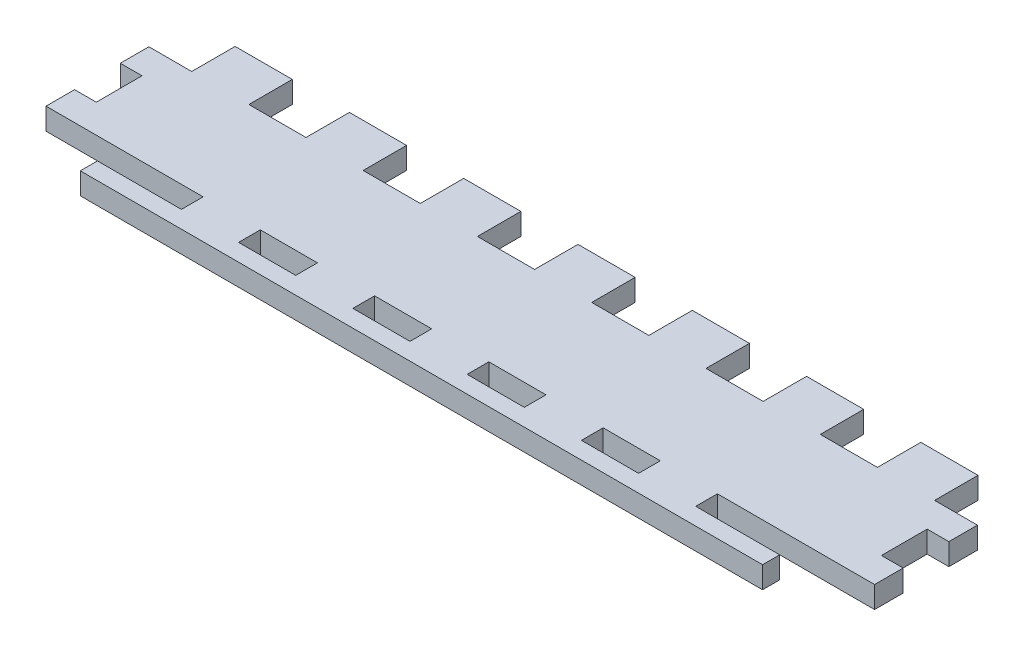
SolidWorks part; units mm, degrees
material "Maple"
ref_plane "Front Plane" through (0, 0, 0) normal (0, 0, 1) x (1, 0, 0)
ref_plane "Top Plane" through (0, 0, 0) normal (0, 1, 0) x (1, 0, 0)
ref_plane "Right Plane" through (0, 0, 0) normal (1, 0, 0) x (0, 0, -1)
sketch "Sketch1" plane through (0, 0, 0) normal (0, 1, 0) x (1, 0, 0)
  line L1 (0, 0) -> (145, 0)
  line L2 (0, 0) -> (0, -18)
  line L3 (0, -18) -> (145, -18)
  line L4 (145, 0) -> (145, -18)
  dimension "D1" = 145
  dimension "D2" = 18
extrude "Boss-Extrude1" add sketch "Sketch1" along normal blind 3.8
sketch "Sketch2" plane through (0, 0, 0) normal (0, -1, 0) x (1, 0, 0)
  line L0 (72.5, 18) -> (72.5, 0) construction
  line L1 (0, 18) -> (145, 18) construction
  line L2 (145, 0) -> (0, 0) construction
  line L4 (67.5, 21.8) -> (77.5, 21.8)
  line L5 (67.5, 21.8) -> (67.5, 18)
  line L6 (67.5, 18) -> (77.5, 18)
  line L7 (77.5, 21.8) -> (77.5, 18)
  line L8 (67.5, 21.8) -> (77.5, 18) construction
  line L9 (67.5, 18) -> (77.5, 21.8) construction
  line L10 (67.5, 0) -> (77.5, 0)
  line L11 (67.5, 0) -> (67.5, -7.6)
  line L12 (67.5, -7.6) -> (77.5, -7.6)
  line L13 (77.5, 0) -> (77.5, -7.6)
  line L14 (67.5, 0) -> (77.5, -7.6) construction
  line L15 (67.5, -7.6) -> (77.5, 0) construction
  point P6 (72.5, 19.9)
  point P11 (72.5, -3.8)
  dimension "D1" = 10
  dimension "D2" = 3.8
  dimension "D3" = 7.6
extrude "Boss-Extrude2" add sketch "Sketch2" against normal through all
pattern_linear "LPattern1" count 4 spacing 20 along (1, 0, 0) count 4 spacing 20 along (-1, 0, 0) of "Boss-Extrude2"
sketch "Sketch3" plane through (0, 3.8, 0) normal (0, 1, 0) x (1, 0, 0)
  line L0 (57.5, -21.8) -> (47.5, -21.8) construction
  line L1 (0, -21.8) -> (145, -21.8)
  line L2 (0, -21.8) -> (0, -24.8)
  line L3 (0, -24.8) -> (145, -24.8)
  line L4 (145, -21.8) -> (145, -24.8)
  line L5 (0, 0) -> (0, -18) construction
  line L6 (145, -18) -> (145, 0) construction
  dimension "D1" = 3
extrude "Boss-Extrude3" add sketch "Sketch3" against normal through all
sketch "Sketch4" plane through (0, 3.8, 0) normal (0, 1, 0) x (1, 0, 0)
  line L9 (7.5, -18) -> (17.5, -18)
  line L10 (7.5, -18) -> (7.5, -21.8)
  line L11 (7.5, -21.8) -> (17.5, -21.8)
  line L12 (17.5, -18) -> (17.5, -21.8)
  line L13 (137.5, -18) -> (127.5, -18)
  line L14 (137.5, -18) -> (137.5, -21.8)
  line L15 (137.5, -21.8) -> (127.5, -21.8)
  line L16 (127.5, -18) -> (127.5, -21.8)
extrude "Cut-Extrude1" cut sketch "Sketch4" against normal through all
sketch "Sketch5" plane through (0, 3.8, 0) normal (0, 1, 0) x (1, 0, 0)
  line L0 (27.5, -21.8) -> (0, -21.8) construction
  line L1 (0, -24.8) -> (12.8, -24.8)
  line L2 (0, -24.8) -> (0, -21.8)
  line L3 (0, -21.8) -> (12.8, -21.8)
  line L4 (12.8, -24.8) -> (12.8, -21.8)
  line L5 (145, -21.8) -> (117.5, -21.8) construction
  line L6 (145, -24.8) -> (132.2, -24.8)
  line L7 (145, -24.8) -> (145, -21.8)
  line L8 (145, -21.8) -> (132.2, -21.8)
  line L9 (132.2, -24.8) -> (132.2, -21.8)
  dimension "D1" = 12.8
extrude "Cut-Extrude2" cut sketch "Sketch5" against normal through all
sketch "Sketch6" plane through (0, 0, 0) normal (0, -1, 0) x (1, 0, 0)
  line L0 (0, 0) -> (0, 18) construction
  line L1 (3.8, 13) -> (0, 13)
  line L2 (3.8, 13) -> (3.8, 5)
  line L3 (3.8, 5) -> (0, 5)
  line L4 (0, 13) -> (0, 5)
  line L10 (145, 18) -> (145, 0) construction
  line L11 (141.2, 13) -> (145, 13)
  line L12 (141.2, 13) -> (141.2, 5)
  line L13 (141.2, 5) -> (145, 5)
  line L14 (145, 13) -> (145, 5)
  line L20 (0, 18) -> (27.5, 18) construction
  line L21 (7.5, 0) -> (0, 0) construction
  dimension "D1" = 5
  dimension "D2" = 3.8
  dimension "D3" = 5
extrude "Cut-Extrude3" cut sketch "Sketch6" against normal through all
